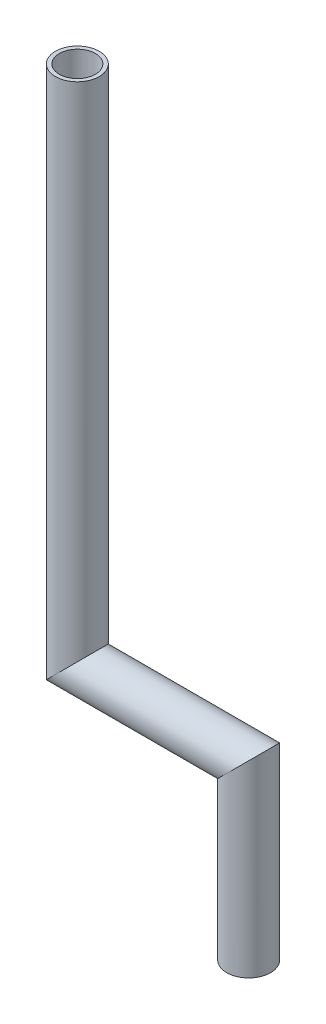
SolidWorks part; units mm, degrees
ref_plane "Front Plane" through (0, 0, 0) normal (0, 0, 1) x (1, 0, 0)
ref_plane "Top Plane" through (0, 0, 0) normal (0, 1, 0) x (1, 0, 0)
ref_plane "Right Plane" through (0, 0, 0) normal (1, 0, 0) x (0, 0, -1)
sketch "Sketch1" plane through (0, 0, 0) normal (0, 0, 1) x (1, 0, 0)
  line L0 (0, 0) -> (99.244, 0)
  line L1 (0, 0) -> (0, 300)
  line L2 (99.244, 0) -> (99.244, -100)
ref_plane "Plane1" through (0, 300, 0) normal (0, 1, 0) x (1, 0, 0)
sketch "Sketch2" plane through (0, 300, 0) normal (0, 1, 0) x (1, 0, 0)
  circle A0 centre (0, 0) radius 12.7
  circle A1 centre (0, 0) radius 10.4583
sweep "Sweep1" add profiles "Sketch2" path "Sketch1"
